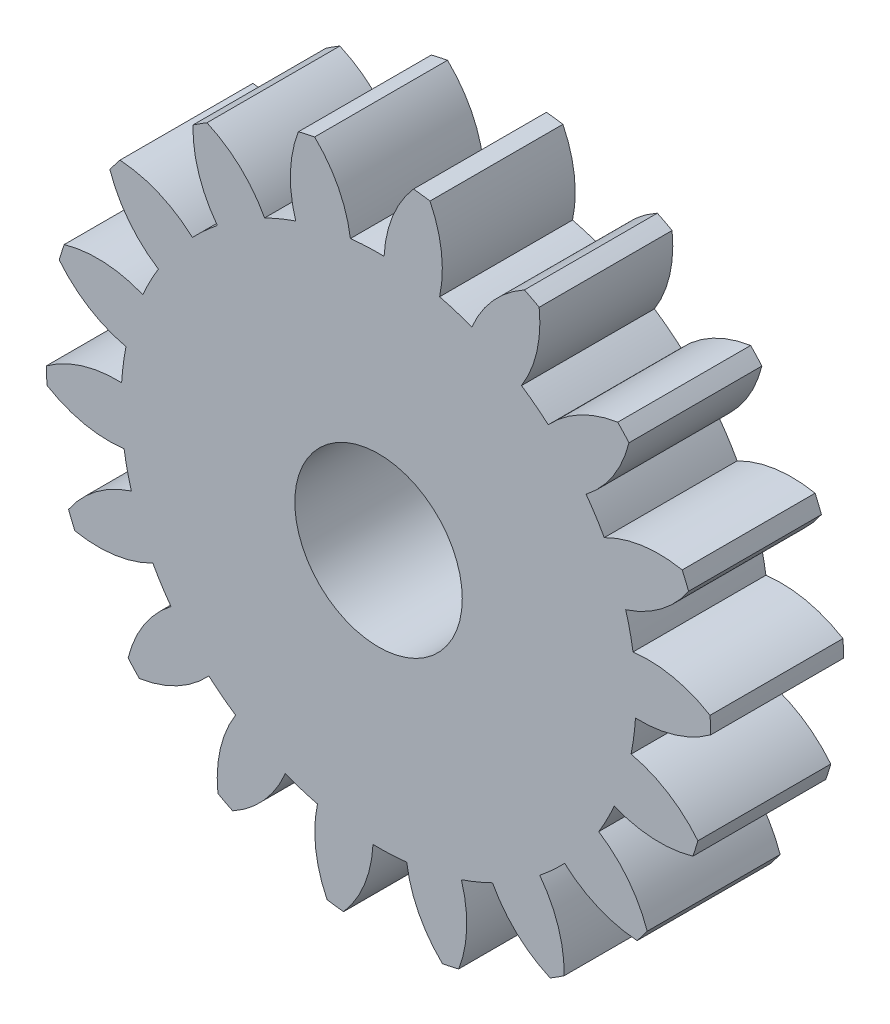
SolidWorks part; units mm, degrees
ref_plane "Front Plane" through (0, 0, 0) normal (0, 0, 1) x (1, 0, 0)
ref_plane "Top Plane" through (0, 0, 0) normal (0, 1, 0) x (1, 0, 0)
ref_plane "Right Plane" through (0, 0, 0) normal (1, 0, 0) x (0, 0, -1)
ref_plane "Plane2" through (0, 0, 46.6167) normal (0, 0, -1) x (-1, 0, 0)
sketch "Sketch5" plane through (0, 0, 46.6167) normal (0, 0, -1) x (-1, 0, 0)
  circle A0 centre (239.2466, -18.5802) radius 0.3969
  arc A1 (246.9211, -32.4768) -> (246.076, -28.8122) centre (241.2398, -31.8572) ccw
  arc A2 (246.076, -28.8122) -> (247.3551, -27.8315) centre (239.2466, -18.5802) ccw
  arc A3 (247.3551, -27.8315) -> (250.6747, -29.5989) centre (251.5511, -23.9515) ccw
  arc A4 (250.6747, -29.5989) -> (251.2112, -29.0139) centre (239.2466, -18.5802) ccw
  arc A5 (251.2112, -29.0139) -> (249.1637, -25.8593) centre (245.6606, -30.3748) ccw
  arc A6 (249.1637, -25.8593) -> (250.0302, -24.5003) centre (239.2466, -18.5802) ccw
  arc A7 (250.0302, -24.5003) -> (253.7541, -25.0258) centre (252.6462, -19.4192) ccw
  arc A8 (253.7541, -25.0258) -> (254.0582, -24.2926) centre (239.2466, -18.5802) ccw
  arc A9 (254.0582, -24.2926) -> (251.0552, -22.0285) centre (249.3078, -27.4698) ccw
  arc A10 (251.0552, -22.0285) -> (251.4047, -20.4551) centre (239.2466, -18.5802) ccw
  arc A11 (251.4047, -20.4551) -> (255.0838, -19.6752) centre (252.1251, -14.7857) ccw
  arc A12 (255.0838, -19.6752) -> (255.1187, -18.8822) centre (239.2466, -18.5802) ccw
  arc A13 (255.1187, -18.8822) -> (251.5225, -17.7817) centre (251.7415, -23.4925) ccw
  arc A14 (251.5225, -17.7817) -> (251.3127, -16.1837) centre (239.2466, -18.5802) ccw
  arc A15 (251.3127, -16.1837) -> (254.5032, -14.1925) centre (250.0506, -10.6098) ccw
  arc A16 (254.5032, -14.1925) -> (254.2648, -13.4354) centre (239.2466, -18.5802) ccw
  arc A17 (254.2648, -13.4354) -> (250.5091, -13.6313) centre (252.6681, -18.9228) ccw
  arc A18 (250.5091, -13.6313) -> (249.7654, -12.2013) centre (239.2466, -18.5802) ccw
  arc A19 (249.7654, -12.2013) -> (252.0824, -9.239) centre (246.673, -7.3953) ccw
  arc A20 (252.0824, -9.239) -> (251.5995, -8.6091) centre (239.2466, -18.5802) ccw
  arc A21 (251.5995, -8.6091) -> (248.1373, -10.0777) centre (251.9758, -14.3117) ccw
  arc A22 (248.1373, -10.0777) -> (246.9494, -8.9884) centre (239.2466, -18.5802) ccw
  arc A23 (246.9494, -8.9884) -> (248.1135, -5.4123) centre (242.3997, -5.5298) ccw
  arc A24 (248.1135, -5.4123) -> (247.4442, -4.9855) centre (239.2466, -18.5802) ccw
  arc A25 (247.4442, -4.9855) -> (244.6931, -7.5497) centre (249.7483, -10.2155) ccw
  arc A26 (244.6931, -7.5497) -> (243.2042, -6.9323) centre (239.2466, -18.5802) ccw
  arc A27 (243.2042, -6.9323) -> (243.075, -3.1737) centre (237.746, -5.2384) ccw
  arc A28 (243.075, -3.1737) -> (242.3002, -3.0016) centre (239.2466, -18.5802) ccw
  arc A29 (242.3002, -3.0016) -> (240.592, -6.3521) centre (246.254, -7.1281) ccw
  arc A30 (240.592, -6.3521) -> (238.9818, -6.2812) centre (239.2466, -18.5802) ccw
  arc A31 (238.9818, -6.2812) -> (237.5748, -2.7934) centre (233.2734, -6.5562) ccw
  arc A32 (237.5748, -2.7934) -> (236.7878, -2.8967) centre (239.2466, -18.5802) ccw
  arc A33 (236.7878, -2.8967) -> (236.3286, -6.6294) centre (241.9146, -5.4221) ccw
  arc A34 (236.3286, -6.6294) -> (234.7912, -7.1134) centre (239.2466, -18.5802) ccw
  arc A35 (234.7912, -7.1134) -> (232.2763, -4.3172) centre (229.5212, -9.3243) ccw
  arc A36 (232.2763, -4.3172) -> (231.5721, -4.6835) centre (239.2466, -18.5802) ccw
  arc A37 (231.5721, -4.6835) -> (232.4172, -8.3481) centre (237.2534, -5.3031) ccw
  arc A38 (232.4172, -8.3481) -> (231.1381, -9.3288) centre (239.2466, -18.5802) ccw
  arc A39 (231.1381, -9.3288) -> (227.8184, -7.5614) centre (226.942, -13.2088) ccw
  arc A40 (227.8184, -7.5614) -> (227.2819, -8.1464) centre (239.2466, -18.5802) ccw
  arc A41 (227.2819, -8.1464) -> (229.3295, -11.301) centre (232.8326, -6.7855) ccw
  arc A42 (229.3295, -11.301) -> (228.4629, -12.66) centre (239.2466, -18.5802) ccw
  arc A43 (228.4629, -12.66) -> (224.739, -12.1345) centre (225.847, -17.7411) ccw
  arc A44 (224.739, -12.1345) -> (224.4349, -12.8678) centre (239.2466, -18.5802) ccw
  arc A45 (224.4349, -12.8678) -> (227.4379, -15.1318) centre (229.1854, -9.6905) ccw
  arc A46 (227.4379, -15.1318) -> (227.0884, -16.7052) centre (239.2466, -18.5802) ccw
  arc A47 (227.0884, -16.7052) -> (223.4094, -17.4851) centre (226.3681, -22.3747) ccw
  arc A48 (223.4094, -17.4851) -> (223.3744, -18.2781) centre (239.2466, -18.5802) ccw
  arc A49 (223.3744, -18.2781) -> (226.9707, -19.3786) centre (226.7517, -13.6678) ccw
  arc A50 (226.9707, -19.3786) -> (227.1804, -20.9766) centre (239.2466, -18.5802) ccw
  arc A51 (227.1804, -20.9766) -> (223.99, -22.9678) centre (228.4425, -26.5505) ccw
  arc A52 (223.99, -22.9678) -> (224.2284, -23.7249) centre (239.2466, -18.5802) ccw
  arc A53 (224.2284, -23.7249) -> (227.9841, -23.529) centre (225.8251, -18.2375) ccw
  arc A54 (227.9841, -23.529) -> (228.7277, -24.959) centre (239.2466, -18.5802) ccw
  arc A55 (228.7277, -24.959) -> (226.4107, -27.9213) centre (231.8201, -29.765) ccw
  arc A56 (226.4107, -27.9213) -> (226.8937, -28.5512) centre (239.2466, -18.5802) ccw
  arc A57 (226.8937, -28.5512) -> (230.3559, -27.0826) centre (226.5173, -22.8486) ccw
  arc A58 (230.3559, -27.0826) -> (231.5438, -28.172) centre (239.2466, -18.5802) ccw
  arc A59 (231.5438, -28.172) -> (230.3797, -31.7481) centre (236.0935, -31.6305) ccw
  arc A60 (230.3797, -31.7481) -> (231.0489, -32.1748) centre (239.2466, -18.5802) ccw
  arc A61 (231.0489, -32.1748) -> (233.8001, -29.6106) centre (228.7449, -26.9449) ccw
  arc A62 (233.8001, -29.6106) -> (235.2889, -30.228) centre (239.2466, -18.5802) ccw
  arc A63 (235.2889, -30.228) -> (235.4181, -33.9866) centre (240.7471, -31.9219) ccw
  arc A64 (235.4181, -33.9866) -> (236.193, -34.1587) centre (239.2466, -18.5802) ccw
  arc A65 (236.193, -34.1587) -> (237.9012, -30.8082) centre (232.2391, -30.0322) ccw
  arc A66 (237.9012, -30.8082) -> (239.5114, -30.8792) centre (239.2466, -18.5802) ccw
  arc A67 (239.5114, -30.8792) -> (240.9183, -34.3669) centre (245.2197, -30.6041) ccw
  arc A68 (240.9183, -34.3669) -> (241.7053, -34.2636) centre (239.2466, -18.5802) ccw
  arc A69 (241.7053, -34.2636) -> (242.1645, -30.5309) centre (236.5785, -31.7382) ccw
  arc A70 (242.1645, -30.5309) -> (243.7019, -30.0469) centre (239.2466, -18.5802) ccw
  arc A71 (243.7019, -30.0469) -> (246.2169, -32.8431) centre (248.9719, -27.836) ccw
  arc A72 (246.2169, -32.8431) -> (246.9211, -32.4768) centre (239.2466, -18.5802) ccw
extrude "Boss-Extrude2" add sketch "Sketch5" against normal blind 6.35 separate body
sketch "Sketch6" plane through (0, 0, 52.9667) normal (0, 0, 1) x (1, 0, 0)
  circle A0 centre (-239.2466, -18.5802) radius 2.9972
  dimension "D1" = 5.9944
extrude "Cut-Extrude1" cut sketch "Sketch6" against normal through all
sketch "Sketch7" plane through (0, 0, 52.9667) normal (0, 0, 1) x (1, 0, 0)
  circle A0 centre (-239.2466, -18.5802) radius 4.0005
  dimension "D1" = 8.001
extrude "Cut-Extrude2" cut sketch "Sketch7" against normal through all
